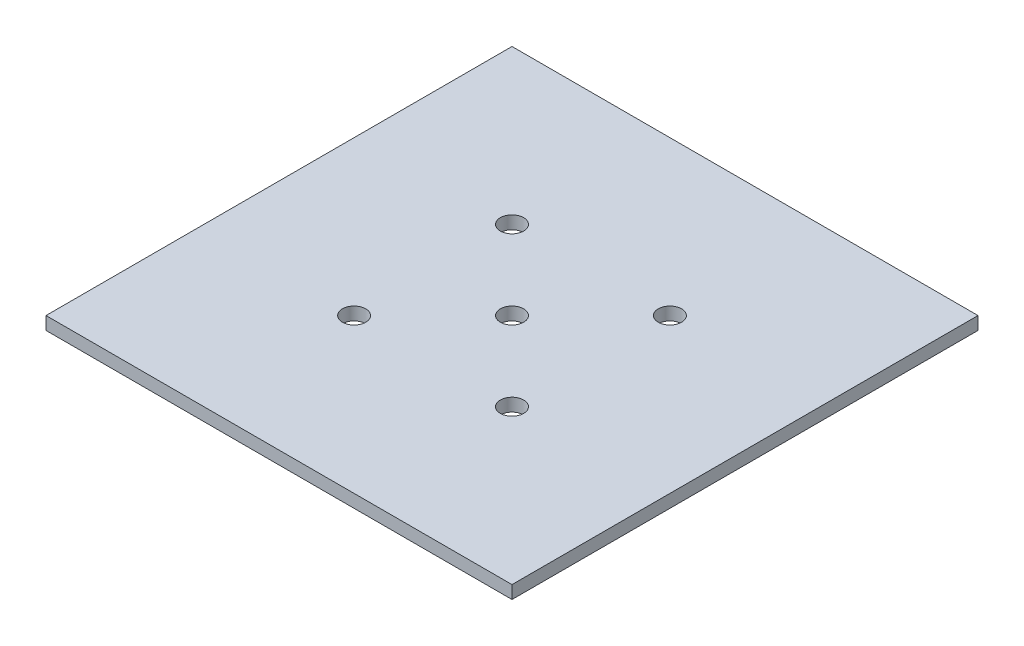
SolidWorks part; units mm, degrees
ref_plane "Front Plane" through (0, 0, 0) normal (0, 0, 1) x (1, 0, 0)
ref_plane "Top Plane" through (0, 0, 0) normal (0, 1, 0) x (1, 0, 0)
ref_plane "Right Plane" through (0, 0, 0) normal (1, 0, 0) x (0, 0, -1)
sketch "Sketch1" plane through (0, 0, 0) normal (0, 1, 0) x (1, 0, 0)
  line L1 (-45, 45) -> (45, 45)
  line L2 (-45, 45) -> (-45, -45)
  line L3 (-45, -45) -> (45, -45)
  line L4 (45, 45) -> (45, -45)
  line L5 (-45, 45) -> (45, -45) construction
  line L6 (-45, -45) -> (45, 45) construction
  line L7 (-15.25, -15.25) -> (15.25, -15.25) construction
  line L8 (-15.25, -15.25) -> (-15.25, 15.25) construction
  line L9 (-15.25, 15.25) -> (15.25, 15.25) construction
  line L10 (15.25, -15.25) -> (15.25, 15.25) construction
  line L11 (-15.25, -15.25) -> (15.25, 15.25) construction
  line L12 (-15.25, 15.25) -> (15.25, -15.25) construction
  point P0 (0, 0)
  point P6 (0, 0)
  dimension "D1" = 90
  dimension "D2" = 30.5
extrude "Boss-Extrude1" add sketch "Sketch1" along normal mid plane 2.5
hole_wizard "M4 Clearance Hole1" positions "Sketch2" profile "Sketch3" hole size "M4" standard "ANSI Metric"
sketch "Sketch2" plane through (0, 1.25, 0) normal (0, 1, 0) x (1, 0, 0)
  line L1 (-15.25, -15.25) -> (15.25, -15.25) construction
  line L2 (-15.25, -15.25) -> (-15.25, 15.25) construction
  line L3 (-15.25, 15.25) -> (15.25, 15.25) construction
  line L4 (15.25, -15.25) -> (15.25, 15.25) construction
  line L5 (-15.25, -15.25) -> (15.25, 15.25) construction
  line L6 (-15.25, 15.25) -> (15.25, -15.25) construction
  point P1 (0, 0)
  point P2 (15.25, 15.25)
  point P73 (-15.25, -15.25)
  point P74 (-15.25, 15.25)
  point P75 (15.25, -15.25)
  dimension "D1" = 30.5
sketch "Sketch3" plane through (0, 1.25, 0) normal (1, 0, 0) x (0, 0, 1)
  line L0 (0, 0) -> (0, 6.5519)
  line L1 (0, 6.5519) -> (2.25, 5.2)
  line L2 (2.25, 5.2) -> (2.25, 0)
  line L5 (2.25, 0) -> (0, 0)
  line L10 (0, 6.5519) -> (-2.25, 5.2) construction
  line L11 (0, -6.35) -> (0, 107.95) construction
  dimension "Hole Dia." = 4.5
  dimension "Hole Depth" = 5.2
  dimension "Drill Angle" = 118
